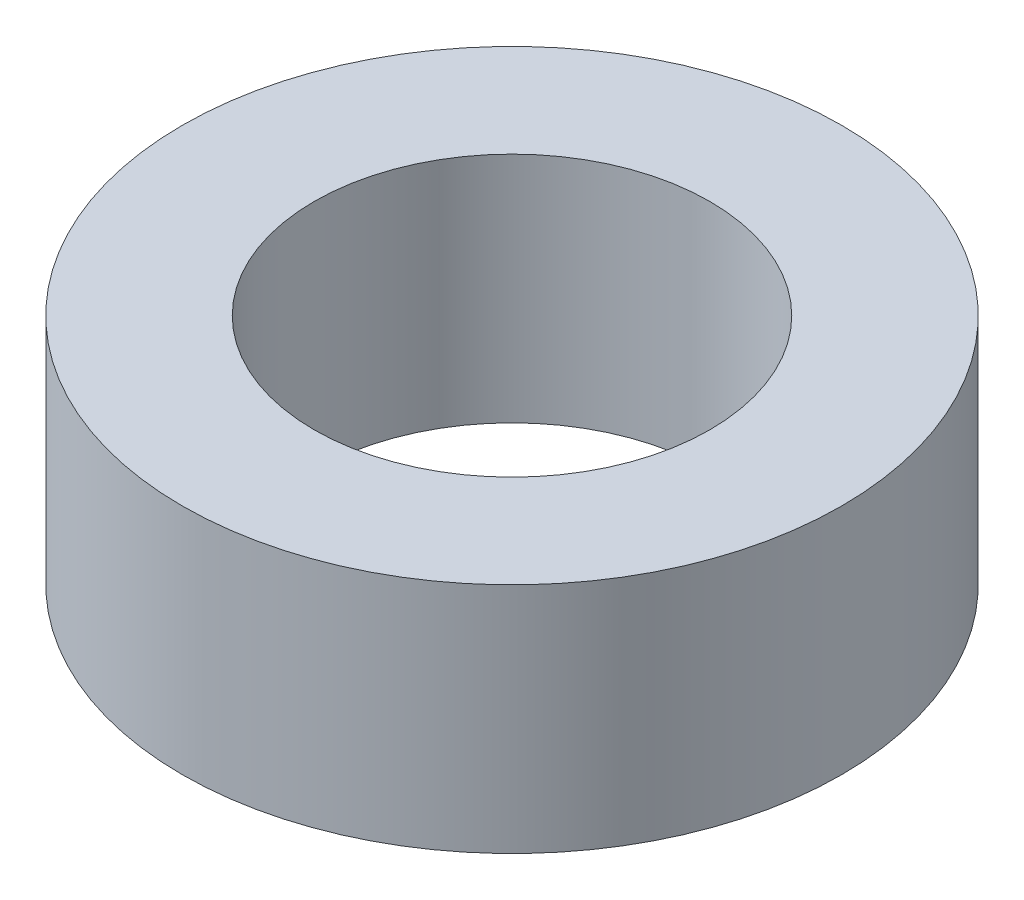
SolidWorks part; units mm, degrees
ref_plane "Front Plane" through (0, 0, 0) normal (0, 0, 1) x (1, 0, 0)
ref_plane "Top Plane" through (0, 0, 0) normal (0, 1, 0) x (1, 0, 0)
ref_plane "Right Plane" through (0, 0, 0) normal (1, 0, 0) x (0, 0, -1)
sketch "Sketch1" plane through (0, 0, 0) normal (0, 1, 0) x (1, 0, 0)
  circle A0 centre (0, 0) radius 17
  circle A1 centre (0, 0) radius 10.2
extrude "Revolved_Equivalent_Extrude" add sketch "Sketch1" along normal blind 12
equation "\"ValveDiameter\" = 50mm"
equation "\"MotorGearTeeth\" = 40"
equation "\"OutputGearTeeth\" = 80"
equation "\"GearModule\" = 1.5mm"
equation "\"PressureAngle\" = 20deg"
equation "\"GearCenterDistance\" = 90mm"
equation "\"GearWidth\" = 18mm"
equation "\"OutputShaftDiameter\" = 20mm"
equation "\"BearingOD\" = 47mm"
equation "\"BearingWidth\" = 14mm"
equation "\"PlateThickness\" = 6mm"
equation "\"ValveRotation\" = 90deg"
